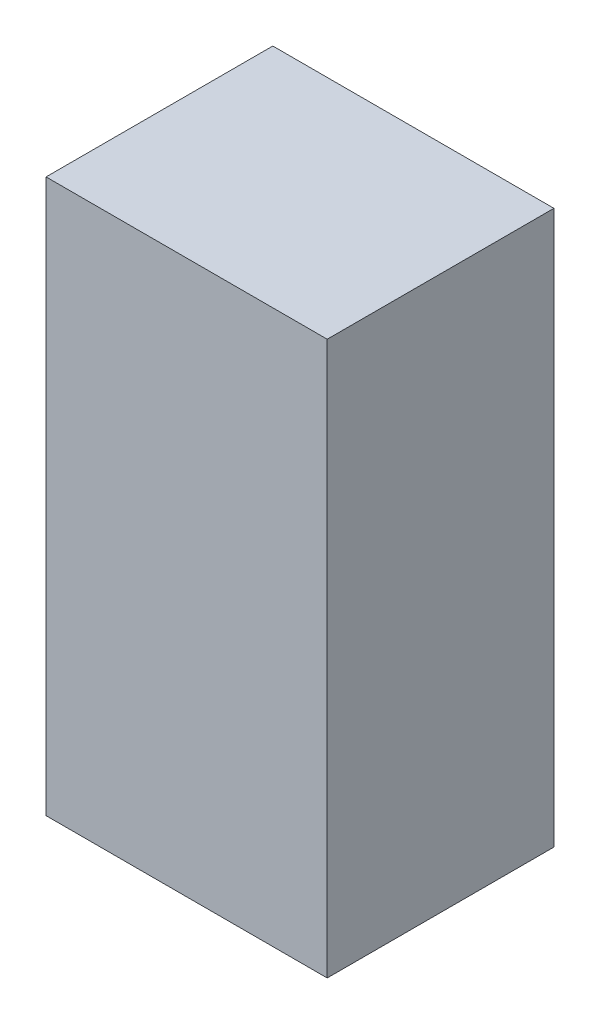
SolidWorks part; units mm, degrees
ref_plane "Front Plane" through (0, 0, 0) normal (0, 0, 1) x (1, 0, 0)
ref_plane "Top Plane" through (0, 0, 0) normal (0, 1, 0) x (1, 0, 0)
ref_plane "Right Plane" through (0, 0, 0) normal (1, 0, 0) x (0, 0, -1)
sketch "Sketch1" plane through (0, 0, 0) normal (0, 0, 1) x (1, 0, 0)
  line L1 (-15.5, -30.5) -> (15.5, -30.5)
  line L2 (-15.5, -30.5) -> (-15.5, 30.5)
  line L3 (-15.5, 30.5) -> (15.5, 30.5)
  line L4 (15.5, -30.5) -> (15.5, 30.5)
  line L5 (-15.5, -30.5) -> (15.5, 30.5) construction
  line L6 (-15.5, 30.5) -> (15.5, -30.5) construction
  point P0 (0, 0)
  dimension "D1" = 61
  dimension "D2" = 31
extrude "Boss-Extrude1" add sketch "Sketch1" along normal blind 25
